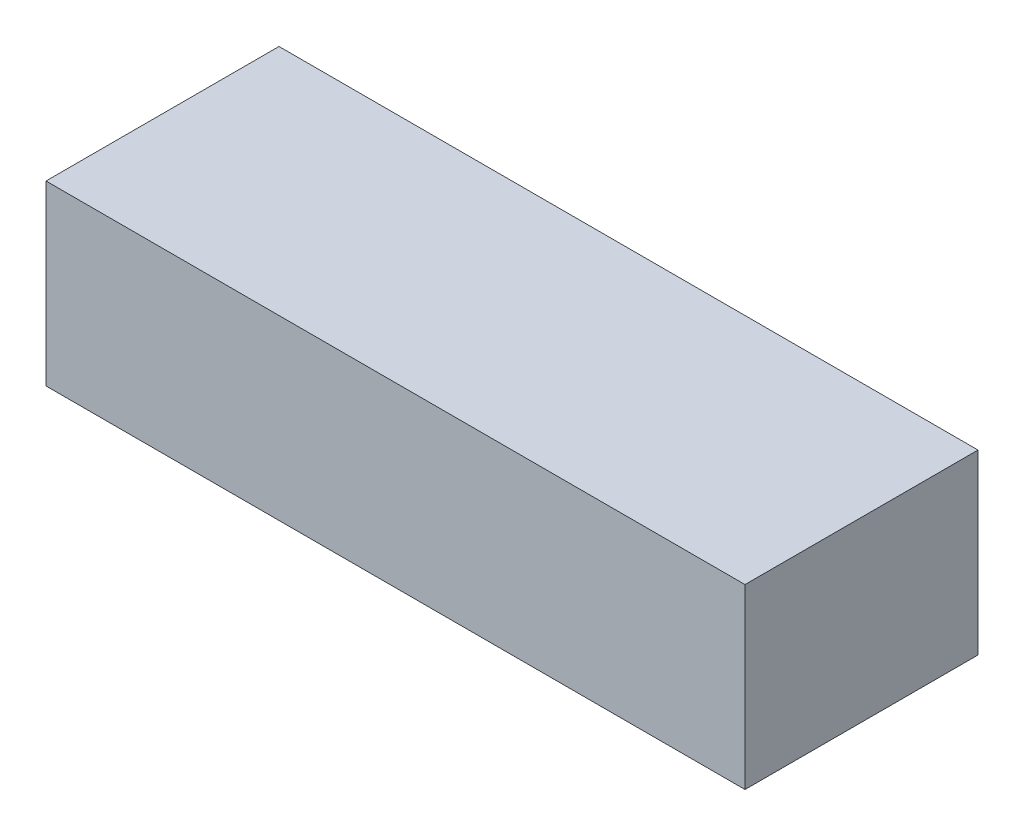
SolidWorks part; units mm, degrees
ref_plane "Plano frontal" through (0, 0, 0) normal (0, 0, 1) x (1, 0, 0)
ref_plane "Plano superior" through (0, 0, 0) normal (0, 1, 0) x (1, 0, 0)
ref_plane "Plano direito" through (0, 0, 0) normal (1, 0, 0) x (0, 0, -1)
sketch "Esboço1" plane through (0, 0, 0) normal (0, 0, 1) x (1, 0, 0)
  line L1 (0, 0) -> (63, 0)
  line L2 (0, 0) -> (0, 16)
  line L3 (0, 16) -> (63, 16)
  line L4 (63, 0) -> (63, 16)
  dimension "D1" = 63
  dimension "D2" = 16
extrude "Ressalto-extrusão1" add sketch "Esboço1" along normal blind 21
